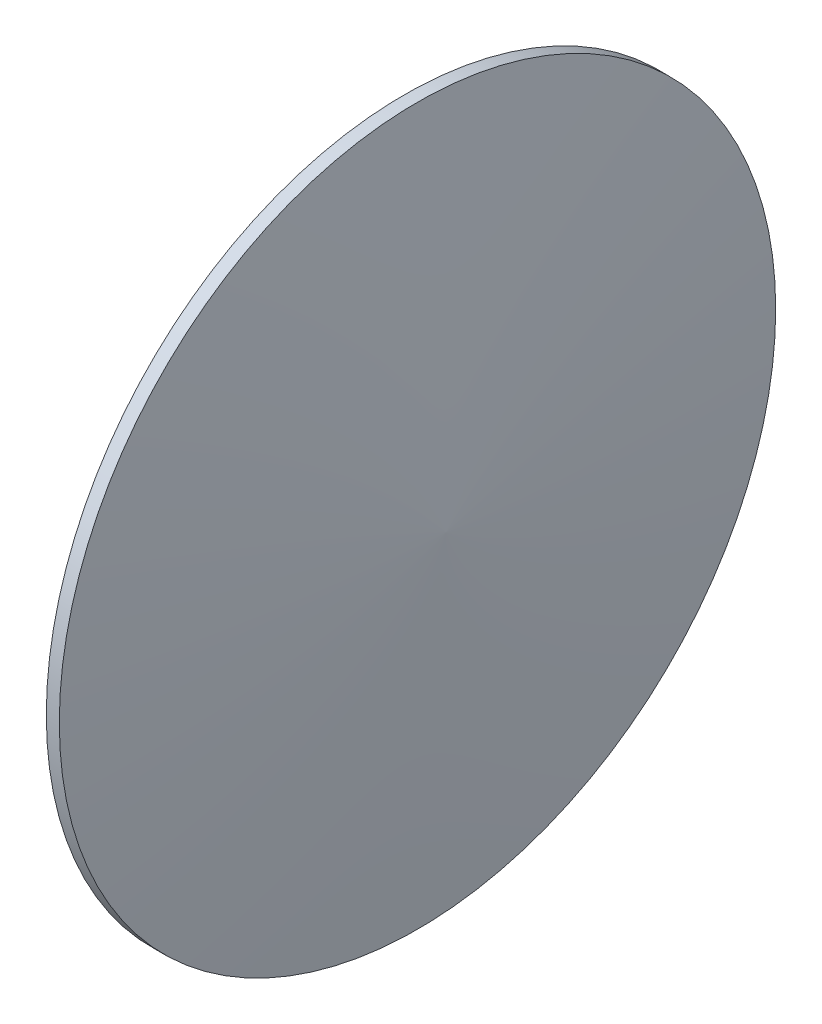
SolidWorks part; units mm, degrees
material "玻璃"
ref_plane "前视基准面" through (0, 0, 0) normal (0, 0, 1) x (1, 0, 0)
ref_plane "上视基准面" through (0, 0, 0) normal (0, 1, 0) x (1, 0, 0)
ref_plane "右视基准面" through (0, 0, 0) normal (1, 0, 0) x (0, 0, -1)
sketch "草图1" plane through (0, 0, 0) normal (0, 0, 1) x (1, 0, 0)
  line L5 (143.214, 13.8406) -> (143.3864, 13.8406)
  line L6 (143.3864, 13.8406) -> (143.214, 13.8406)
  line L8 (143.3251, 9.0906) -> (143.7657, 9.0906)
  line L9 (143.7657, 9.0906) -> (142.7209, 9.0906)
  arc A1 (143.214, 13.8406) -> (142.7209, 9.0906) centre (253.408, 0) ccw
  arc A3 (143.7657, 9.0906) -> (143.3864, 13.8406) centre (0, 0) ccw
revolve "旋转1" add sketch "草图1" angle 360 about L9
